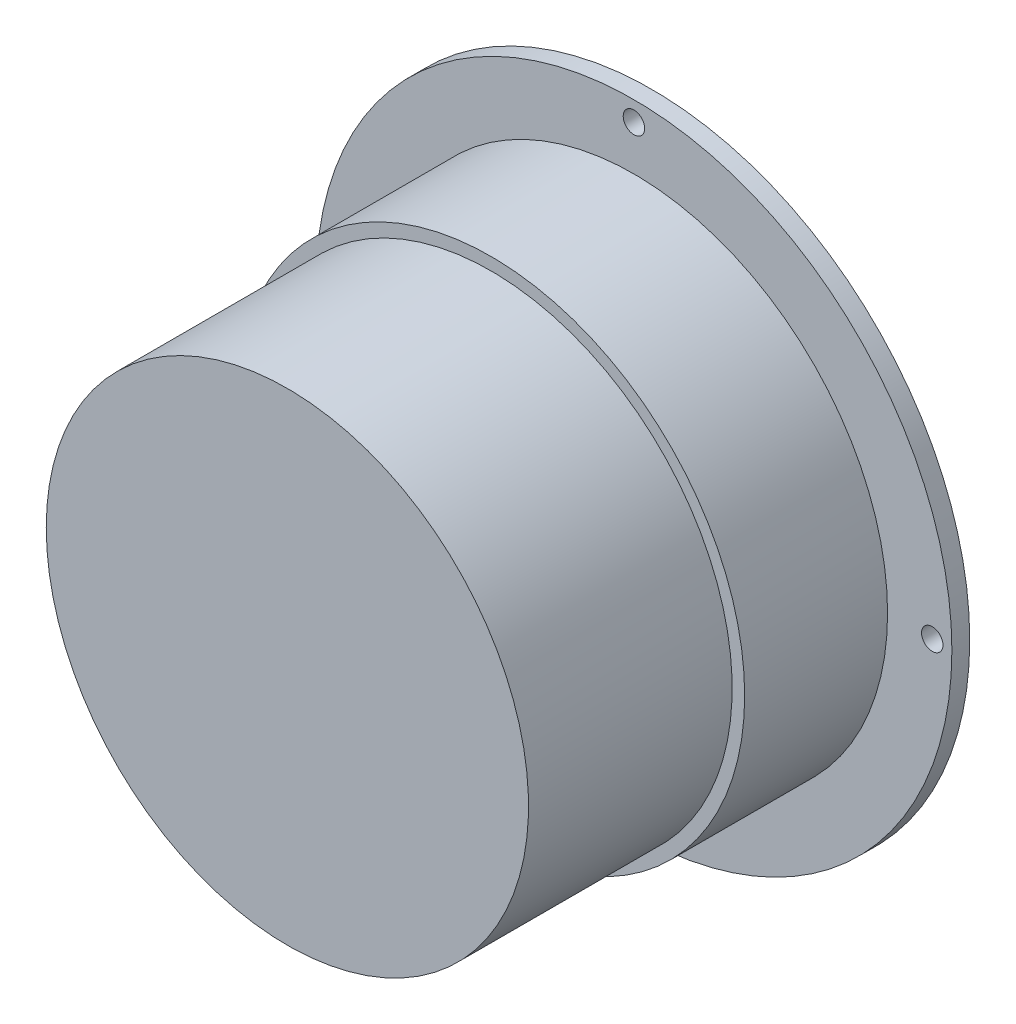
SolidWorks part; units mm, degrees
material "A-Glass Fiber"
ref_plane "Front Plane" through (0, 0, 0) normal (0, 0, 1) x (1, 0, 0)
ref_plane "Top Plane" through (0, 0, 0) normal (0, 1, 0) x (1, 0, 0)
ref_plane "Right Plane" through (0, 0, 0) normal (1, 0, 0) x (0, 0, -1)
sketch "Sketch1" plane through (0, 0, 0) normal (0, 0, 1) x (1, 0, 0)
  circle A0 centre (0, 0) radius 44.5
  dimension "D1" = 89
extrude "Boss-Extrude1" add sketch "Sketch1" along normal blind 2.5
sketch "Sketch2" plane through (0, 0, 2.5) normal (0, 0, 1) x (1, 0, 0)
  circle A0 centre (0, 0) radius 41.75 construction
  circle A1 centre (0, 41.75) radius 1.5
  circle A2 centre (41.75, 0) radius 1.5
  circle A3 centre (0, -41.75) radius 1.5
  circle A4 centre (-41.75, 0) radius 1.5
  point P14 (0, 0)
  dimension "D1" = 83.5
  dimension "D2" = 3
  dimension "D3" = 4
extrude "Cut-Extrude1" cut sketch "Sketch2" against normal through all
sketch "Sketch3" plane through (0, 0, 2.5) normal (0, 0, 1) x (1, 0, 0)
  circle A0 centre (0, 0) radius 35.5
  dimension "D1" = 71
extrude "Boss-Extrude2" add sketch "Sketch3" along normal blind 20
sketch "Sketch4" plane through (0, 0, 22.5) normal (0, 0, 1) x (1, 0, 0)
  circle A0 centre (0, 0) radius 33.75
  dimension "D1" = 67.5
extrude "Boss-Extrude3" add sketch "Sketch4" along normal blind 28.5
